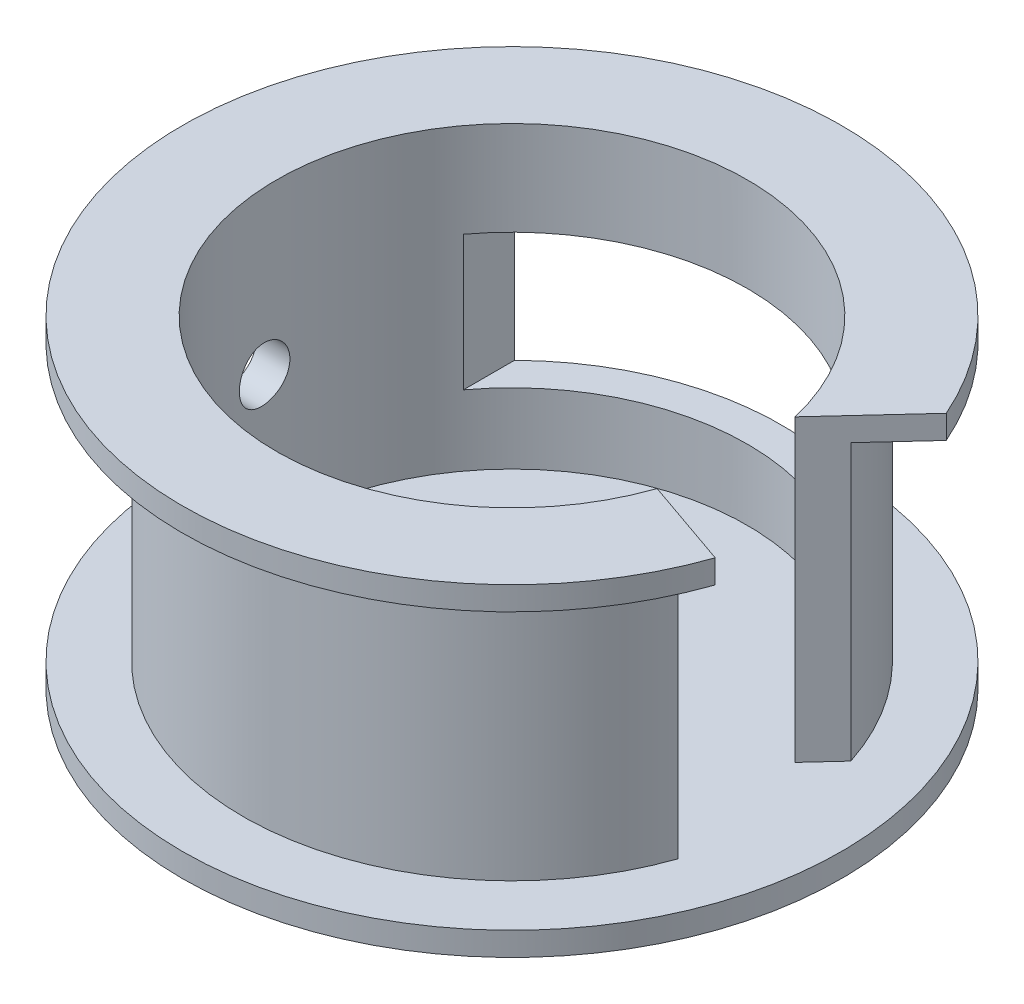
SolidWorks part; units mm, degrees
ref_plane "Front Plane" through (0, 0, 0) normal (0, 0, 1) x (1, 0, 0)
ref_plane "Top Plane" through (0, 0, 0) normal (0, 1, 0) x (1, 0, 0)
ref_plane "Right Plane" through (0, 0, 0) normal (1, 0, 0) x (0, 0, -1)
sketch "Sketch1" plane through (0, 0, 0) normal (0, 1, 0) x (1, 0, 0)
  circle A0 centre (0, 0) radius 4.9
extrude "Boss-Extrude1" add sketch "Sketch1" along normal blind 0.35
sketch "Sketch3" plane through (0, 0.35, 0) normal (0, 1, 0) x (1, 0, 0)
  circle A0 centre (0, 0) radius 4
  circle A1 centre (0, 0) radius 3.5
extrude "Boss-Extrude2" add sketch "Sketch3" along normal blind 4.1
sketch "Sketch4" plane through (0, 4.45, 0) normal (0, 1, 0) x (1, 0, 0)
  circle A0 centre (0, 0) radius 4.9
  circle A1 centre (0, 0) radius 3.5
extrude "Boss-Extrude3" add sketch "Sketch4" along normal blind 0.35
sketch "Sketch5" plane through (0, 4.8, 0) normal (0, 1, 0) x (1, 0, 0)
  line L1 (3.4071, 0.8012) -> (4.4857, 1.972)
  line L2 (3.3064, -1.1478) -> (4.629, -1.6069)
  circle A0 centre (0, 0) radius 3.5
  circle A1 centre (0, 0) radius 4.9 construction
  circle A2 centre (0, 0) radius 4.9
  circle M4 centre (0, 0) radius 4.9
  circle M5 centre (0, 0) radius 3.5
extrude "Cut-Extrude1" cut sketch "Sketch5" against normal blind 4.45 contours L2 L1 M5 M4
sketch "Sketch7" plane through (0, 0, 0) normal (0, 0, 1) x (1, 0, 0)
  line L1 (1.8539, 3.4) -> (-2.8097, 3.4)
  line L2 (1.8539, 3.4) -> (1.8539, 1.3965)
  line L4 (1.8539, 1.3965) -> (-2.8097, 1.3965)
  line L5 (-2.8097, 3.4) -> (-2.8097, 1.3965)
extrude "Cut-Extrude2" cut sketch "Sketch7" against normal blind 11.45
sketch "Sketch8" plane through (0, 0.35, 0) normal (0, 1, 0) x (1, 0, 0)
  circle A0 centre (0, 0) radius 1.6
extrude "Cut-Extrude3" cut sketch "Sketch8" against normal blind 11.45
sketch "Sketch9" plane through (0, 0, 0) normal (1, 0, 0) x (0, 0, -1)
  line L0 (-0.2072, 4.8) -> (-0.2072, 0)
  line L1 (3.5, 4.8) -> (-3.5, 4.8) construction
  line L2 (-4.9, 0) -> (4.9, 0) construction
  circle A0 centre (-0.2072, 2.4) radius 0.4
extrude "Cut-Extrude5" cut sketch "Sketch9" against normal blind 11.45 contours L0 A0 | L0 A0
